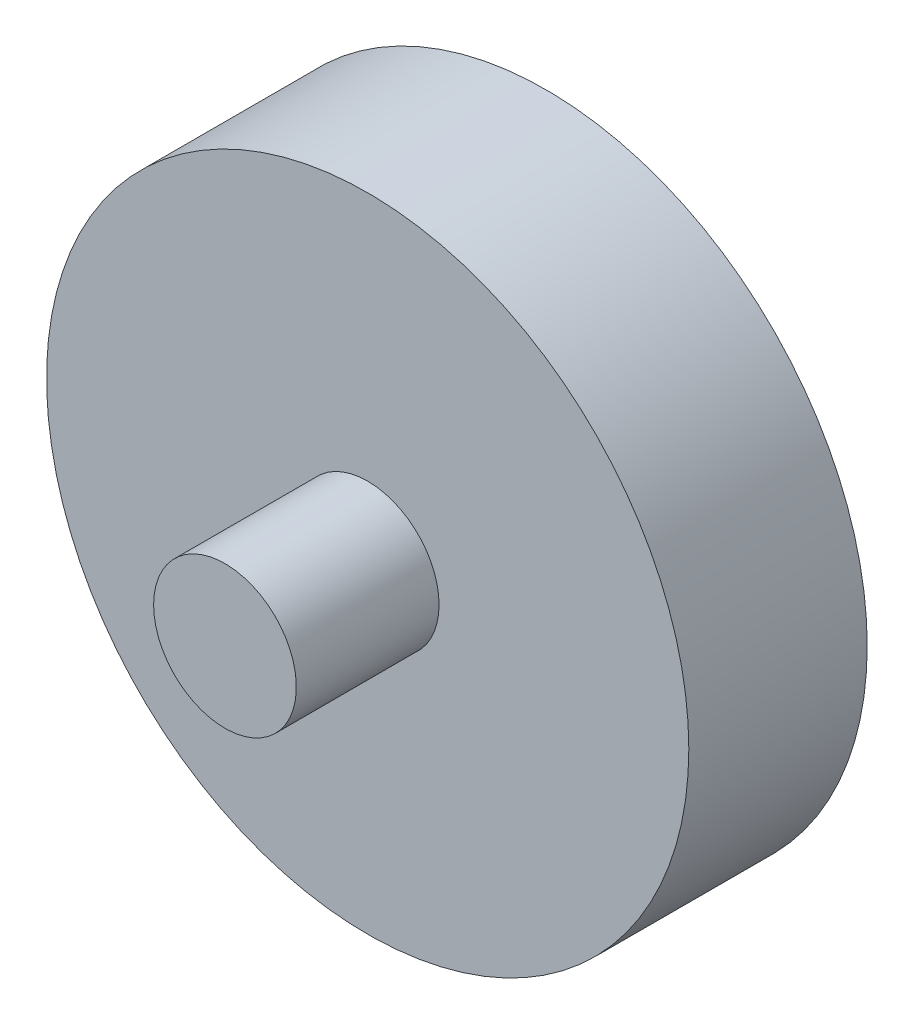
SolidWorks part; units mm, degrees
ref_plane "Front Plane" through (0, 0, 0) normal (0, 0, 1) x (1, 0, 0)
ref_plane "Top Plane" through (0, 0, 0) normal (0, 1, 0) x (1, 0, 0)
ref_plane "Right Plane" through (0, 0, 0) normal (1, 0, 0) x (0, 0, -1)
sketch "Sketch1" plane through (0, 0, 0) normal (0, 0, 1) x (1, 0, 0)
  circle A0 centre (0, 0) radius 11.43
  dimension "D1" = 22.86
extrude "main body" add sketch "Sketch1" along normal blind 6.35
sketch "Sketch13" plane through (0, 0, 0) normal (0, 0, -1) x (-1, 0, 0)
  circle A0 centre (0, 0) radius 2.54
extrude "nibbles" add sketch "Sketch13" along normal blind 5.08 and the other way blind 11.43
